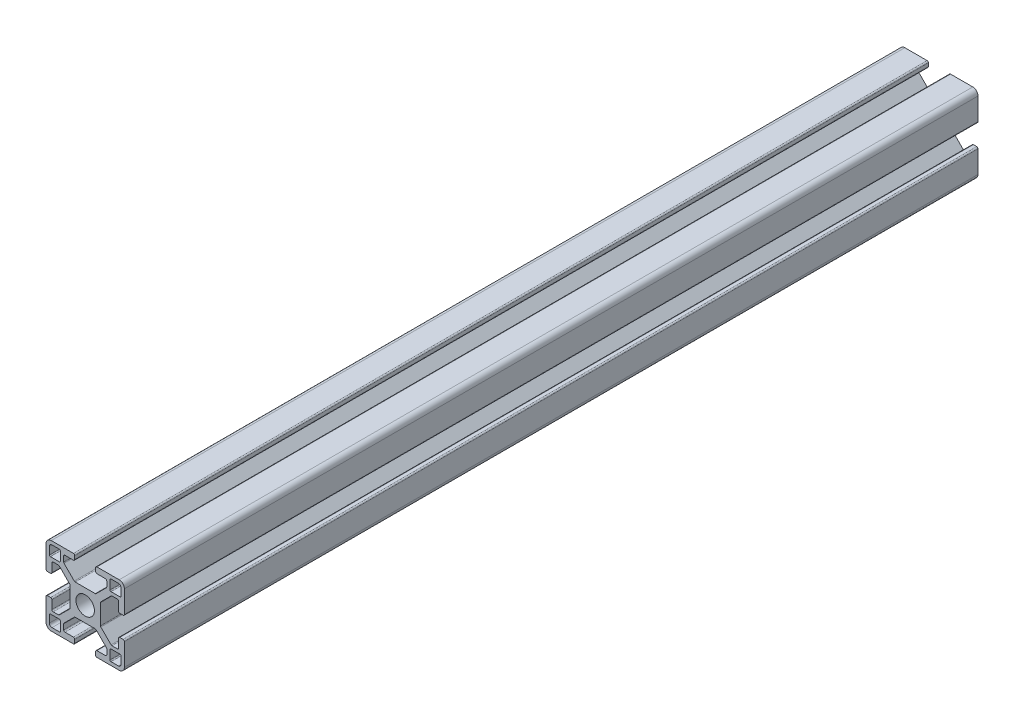
SolidWorks part; units mm, degrees
ref_plane "Front Plane" through (0, 0, 0) normal (0, 0, 1) x (1, 0, 0)
ref_plane "Top Plane" through (0, 0, 0) normal (0, 1, 0) x (1, 0, 0)
ref_plane "Right Plane" through (0, 0, 0) normal (1, 0, 0) x (0, 0, -1)
sketch "Sketch1" plane through (0, 0, 0) normal (0, 0, 1) x (1, 0, 0)
  line L0 (3.9799, -2.4733) -> (3.1981, -1.4942) construction
  line L1 (1.4942, -3.1981) -> (2.4733, -3.9799) construction
  line L2 (-2.4733, -3.9799) -> (-1.4942, -3.1981) construction
  line L3 (-3.1981, -1.4942) -> (-3.9799, -2.4733) construction
  line L4 (-3.9799, 2.4733) -> (-3.1981, 1.4942) construction
  line L5 (-1.4942, 3.1981) -> (-2.4733, 3.9799) construction
  line L6 (2.4733, 3.9799) -> (1.4942, 3.1981) construction
  line L7 (3.1981, 1.4942) -> (3.9799, 2.4733) construction
  line L8 (-12.6999, -13.6999) -> (-9.881, -13.6999)
  line L9 (-13.6999, -9.881) -> (-13.6999, -12.6999)
  line L10 (-9.88, -9.5) -> (-13.3189, -9.5)
  line L11 (-9.5, -13.3189) -> (-9.5, -9.88)
  line L12 (13.6999, -12.6999) -> (13.6999, -9.881)
  line L13 (9.881, -13.6999) -> (12.6999, -13.6999)
  line L14 (9.5, -9.88) -> (9.5, -13.3189)
  line L15 (13.3189, -9.5) -> (9.88, -9.5)
  line L16 (9.88, 9.5) -> (13.3189, 9.5)
  line L17 (9.5, 13.3189) -> (9.5, 9.88)
  line L18 (12.6999, 13.6999) -> (9.881, 13.6999)
  line L19 (13.6999, 9.881) -> (13.6999, 12.6999)
  line L20 (-13.6999, 12.6999) -> (-13.6999, 9.881)
  line L21 (-9.881, 13.6999) -> (-12.6999, 13.6999)
  line L22 (-9.5, 9.88) -> (-9.5, 13.3189)
  line L23 (-13.3189, 9.5) -> (-9.88, 9.5)
  line L24 (14.4999, -4) -> (13.2425, -4)
  line L25 (12.7425, -4.5) -> (12.7425, -7.7325)
  line L26 (12.2428, -8.25) -> (10.2602, -8.25)
  line L27 (9.9066, -8.1035) -> (5.9811, -4.178)
  line L28 (5.8347, -3.8245) -> (5.8347, -1.0125)
  line L29 (5.8347, -1.0125) -> (5.3247, -0.0625) construction
  line L30 (5.3247, -0.0625) -> (5.8347, 0.8875) construction
  line L31 (5.8347, 0.8875) -> (5.8347, 3.8245)
  line L32 (5.9811, 4.178) -> (9.9066, 8.1035)
  line L33 (10.2602, 8.25) -> (12.2428, 8.25)
  line L34 (12.7425, 7.7325) -> (12.7425, 4.5)
  line L35 (13.2425, 4) -> (14.4999, 4)
  line L36 (14.9999, 4.5) -> (14.9999, 12.9999)
  line L37 (12.9999, 14.9999) -> (4.5, 14.9999)
  line L38 (4, 14.4999) -> (4, 13.2425)
  line L39 (4.5, 12.7425) -> (7.7325, 12.7425)
  line L40 (8.25, 12.2428) -> (8.25, 10.2602)
  line L41 (8.1035, 9.9066) -> (4.178, 5.9811)
  line L42 (3.8245, 5.8347) -> (0.95, 5.8347)
  line L43 (0.95, 5.8347) -> (0, 5.3247) construction
  line L44 (0, 5.3247) -> (-0.95, 5.8347) construction
  line L45 (-0.95, 5.8347) -> (-3.8245, 5.8347)
  line L46 (-4.178, 5.9811) -> (-8.1035, 9.9066)
  line L47 (-8.25, 10.2602) -> (-8.25, 12.2428)
  line L48 (-7.7325, 12.7425) -> (-4.5, 12.7425)
  line L49 (-4, 13.2425) -> (-4, 14.4999)
  line L50 (-4.5, 14.9999) -> (-12.9999, 14.9999)
  line L51 (-14.9999, 12.9999) -> (-14.9999, 4.5)
  line L52 (-14.4999, 4) -> (-13.2425, 4)
  line L53 (-12.7425, 4.5) -> (-12.7425, 7.7325)
  line L54 (-12.2428, 8.25) -> (-10.2602, 8.25)
  line L55 (-9.9066, 8.1035) -> (-5.9811, 4.178)
  line L56 (-5.8347, 3.8245) -> (-5.8347, 0.8875)
  line L57 (-5.8347, 0.8875) -> (-5.3247, -0.0625) construction
  line L58 (-5.3247, -0.0625) -> (-5.8347, -1.0125) construction
  line L59 (-5.8347, -1.0125) -> (-5.8347, -3.8245)
  line L60 (-5.9811, -4.178) -> (-9.9066, -8.1035)
  line L61 (-10.2602, -8.25) -> (-12.2428, -8.25)
  line L62 (-12.7425, -7.7325) -> (-12.7425, -4.5)
  line L63 (-13.2425, -4) -> (-14.4999, -4)
  line L64 (-14.9999, -4.5) -> (-14.9999, -12.9999)
  line L65 (-12.9999, -14.9999) -> (-4.5, -14.9999)
  line L66 (-4, -14.4999) -> (-4, -13.2425)
  line L67 (-4.5, -12.7425) -> (-7.7325, -12.7425)
  line L68 (-8.25, -12.2428) -> (-8.25, -10.2602)
  line L69 (-8.1035, -9.9066) -> (-4.178, -5.9811)
  line L70 (-3.8245, -5.8347) -> (-0.95, -5.8347)
  line L71 (-0.95, -5.8347) -> (0, -5.3247) construction
  line L72 (0, -5.3247) -> (0.95, -5.8347) construction
  line L73 (0.95, -5.8347) -> (3.8245, -5.8347)
  line L74 (4.178, -5.9811) -> (8.1035, -9.9066)
  line L75 (8.25, -10.2602) -> (8.25, -12.2428)
  line L76 (7.7325, -12.7425) -> (4.5, -12.7425)
  line L77 (4, -13.2425) -> (4, -14.4999)
  line L78 (4.5, -14.9999) -> (12.9999, -14.9999)
  line L79 (14.9999, -12.9999) -> (14.9999, -4.5)
  line L80 (-5.8347, -1.0125) -> (-5.8347, 0.8875)
  line L81 (-0.95, 5.8347) -> (0.95, 5.8347)
  line L82 (5.8347, 0.8875) -> (5.8347, -1.0125)
  line L83 (-0.95, -5.8347) -> (0.95, -5.8347)
  arc A0 (2.4733, -3.9799) -> (3.9799, -2.4733) centre (3.1422, -3.1422) ccw construction
  arc A1 (-1.4942, -3.1981) -> (1.4942, -3.1981) centre (0, 0) ccw construction
  arc A2 (-3.9799, -2.4733) -> (-2.4733, -3.9799) centre (-3.1422, -3.1422) ccw construction
  arc A3 (-3.1981, 1.4942) -> (-3.1981, -1.4942) centre (0, 0) ccw construction
  arc A4 (-2.4733, 3.9799) -> (-3.9799, 2.4733) centre (-3.1422, 3.1422) ccw construction
  arc A5 (1.4942, 3.1981) -> (-1.4942, 3.1981) centre (0, 0) ccw construction
  arc A6 (3.9799, 2.4733) -> (2.4733, 3.9799) centre (3.1422, 3.1422) ccw construction
  arc A7 (3.1981, -1.4942) -> (3.1981, 1.4942) centre (0, 0) ccw construction
  arc A8 (-13.6999, -12.6999) -> (-12.6999, -13.6999) centre (-12.6999, -12.6999) ccw
  arc A9 (-13.3189, -9.5) -> (-13.6999, -9.881) centre (-13.3189, -9.881) ccw
  arc A10 (-9.5, -9.88) -> (-9.88, -9.5) centre (-9.88, -9.88) ccw
  arc A11 (-9.881, -13.6999) -> (-9.5, -13.3189) centre (-9.881, -13.3189) ccw
  arc A12 (12.6999, -13.6999) -> (13.6999, -12.6999) centre (12.6999, -12.6999) ccw
  arc A13 (9.5, -13.3189) -> (9.881, -13.6999) centre (9.881, -13.3189) ccw
  arc A14 (9.88, -9.5) -> (9.5, -9.88) centre (9.88, -9.88) ccw
  arc A15 (13.6999, -9.881) -> (13.3189, -9.5) centre (13.3189, -9.881) ccw
  arc A16 (9.5, 9.88) -> (9.88, 9.5) centre (9.88, 9.88) ccw
  arc A17 (9.881, 13.6999) -> (9.5, 13.3189) centre (9.881, 13.3189) ccw
  arc A18 (13.6999, 12.6999) -> (12.6999, 13.6999) centre (12.6999, 12.6999) ccw
  arc A19 (13.3189, 9.5) -> (13.6999, 9.881) centre (13.3189, 9.881) ccw
  arc A20 (14.9999, -4.5) -> (14.4999, -4) centre (14.4999, -4.5) ccw
  arc A21 (13.2425, -4) -> (12.7425, -4.5) centre (13.2425, -4.5) ccw
  arc A22 (12.2428, -8.25) -> (12.7425, -7.7325) centre (12.2428, -7.75) ccw
  arc A23 (9.9066, -8.1035) -> (10.2602, -8.25) centre (10.2602, -7.75) ccw
  arc A24 (5.8347, -3.8245) -> (5.9811, -4.178) centre (6.3347, -3.8245) ccw
  arc A25 (5.9811, 4.178) -> (5.8347, 3.8245) centre (6.3347, 3.8245) ccw
  arc A26 (10.2602, 8.25) -> (9.9066, 8.1035) centre (10.2602, 7.75) ccw
  arc A27 (12.7425, 7.7325) -> (12.2428, 8.25) centre (12.2428, 7.75) ccw
  arc A28 (12.7425, 4.5) -> (13.2425, 4) centre (13.2425, 4.5) ccw
  arc A29 (14.4999, 4) -> (14.9999, 4.5) centre (14.4999, 4.5) ccw
  arc A30 (14.9999, 12.9999) -> (12.9999, 14.9999) centre (12.9999, 12.9999) ccw
  arc A31 (4.5, 14.9999) -> (4, 14.4999) centre (4.5, 14.4999) ccw
  arc A32 (4, 13.2425) -> (4.5, 12.7425) centre (4.5, 13.2425) ccw
  arc A33 (8.25, 12.2428) -> (7.7325, 12.7425) centre (7.75, 12.2428) ccw
  arc A34 (8.1035, 9.9066) -> (8.25, 10.2602) centre (7.75, 10.2602) ccw
  arc A35 (3.8245, 5.8347) -> (4.178, 5.9811) centre (3.8245, 6.3347) ccw
  arc A36 (-4.178, 5.9811) -> (-3.8245, 5.8347) centre (-3.8245, 6.3347) ccw
  arc A37 (-8.25, 10.2602) -> (-8.1035, 9.9066) centre (-7.75, 10.2602) ccw
  arc A38 (-7.7325, 12.7425) -> (-8.25, 12.2428) centre (-7.75, 12.2428) ccw
  arc A39 (-4.5, 12.7425) -> (-4, 13.2425) centre (-4.5, 13.2425) ccw
  arc A40 (-4, 14.4999) -> (-4.5, 14.9999) centre (-4.5, 14.4999) ccw
  arc A41 (-12.9999, 14.9999) -> (-14.9999, 12.9999) centre (-12.9999, 12.9999) ccw
  arc A42 (-14.9999, 4.5) -> (-14.4999, 4) centre (-14.4999, 4.5) ccw
  arc A43 (-13.2425, 4) -> (-12.7425, 4.5) centre (-13.2425, 4.5) ccw
  arc A44 (-12.2428, 8.25) -> (-12.7425, 7.7325) centre (-12.2428, 7.75) ccw
  arc A45 (-9.9066, 8.1035) -> (-10.2602, 8.25) centre (-10.2602, 7.75) ccw
  arc A46 (-5.8347, 3.8245) -> (-5.9811, 4.178) centre (-6.3347, 3.8245) ccw
  arc A47 (-5.9811, -4.178) -> (-5.8347, -3.8245) centre (-6.3347, -3.8245) ccw
  arc A48 (-10.2602, -8.25) -> (-9.9066, -8.1035) centre (-10.2602, -7.75) ccw
  arc A49 (-12.7425, -7.7325) -> (-12.2428, -8.25) centre (-12.2428, -7.75) ccw
  arc A50 (-12.7425, -4.5) -> (-13.2425, -4) centre (-13.2425, -4.5) ccw
  arc A51 (-14.4999, -4) -> (-14.9999, -4.5) centre (-14.4999, -4.5) ccw
  arc A52 (-14.9999, -12.9999) -> (-12.9999, -14.9999) centre (-12.9999, -12.9999) ccw
  arc A53 (-4.5, -14.9999) -> (-4, -14.4999) centre (-4.5, -14.4999) ccw
  arc A54 (-4, -13.2425) -> (-4.5, -12.7425) centre (-4.5, -13.2425) ccw
  arc A55 (-8.25, -12.2428) -> (-7.7325, -12.7425) centre (-7.75, -12.2428) ccw
  arc A56 (-8.1035, -9.9066) -> (-8.25, -10.2602) centre (-7.75, -10.2602) ccw
  arc A57 (-3.8245, -5.8347) -> (-4.178, -5.9811) centre (-3.8245, -6.3347) ccw
  arc A58 (4.178, -5.9811) -> (3.8245, -5.8347) centre (3.8245, -6.3347) ccw
  arc A59 (8.25, -10.2602) -> (8.1035, -9.9066) centre (7.75, -10.2602) ccw
  arc A60 (7.7325, -12.7425) -> (8.25, -12.2428) centre (7.75, -12.2428) ccw
  arc A61 (4.5, -12.7425) -> (4, -13.2425) centre (4.5, -13.2425) ccw
  arc A62 (4, -14.4999) -> (4.5, -14.9999) centre (4.5, -14.4999) ccw
  arc A63 (12.9999, -14.9999) -> (14.9999, -12.9999) centre (12.9999, -12.9999) ccw
  arc A64 (-12.6999, 13.6999) -> (-13.6999, 12.6999) centre (-12.6999, 12.6999) ccw
  arc A65 (-9.5, 13.3189) -> (-9.881, 13.6999) centre (-9.881, 13.3189) ccw
  arc A66 (-9.88, 9.5) -> (-9.5, 9.88) centre (-9.88, 9.88) ccw
  arc A67 (-13.6999, 9.881) -> (-13.3189, 9.5) centre (-13.3189, 9.881) ccw
  circle A68 centre (0, 0) radius 3.53
extrude "Boss-Extrude1" add sketch "Sketch1" along normal mid plane 326.644
